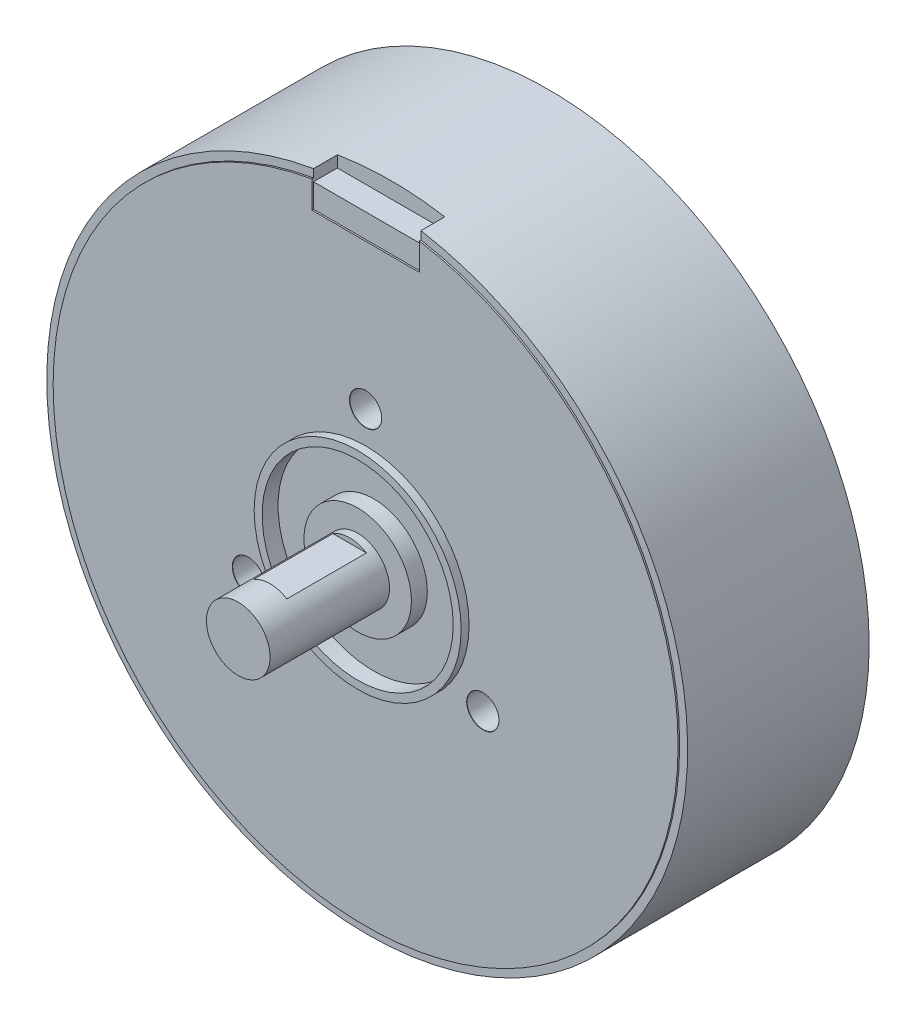
SolidWorks part; units mm, degrees
ref_plane "Front Plane" through (0, 0, 0) normal (0, 0, 1) x (1, 0, 0)
ref_plane "Top Plane" through (0, 0, 0) normal (0, 1, 0) x (1, 0, 0)
ref_plane "Right Plane" through (0, 0, 0) normal (1, 0, 0) x (0, 0, -1)
sketch "Sketch1" plane through (0, 0, 0) normal (0, 0, 1) x (1, 0, 0)
  circle A0 centre (0, 0) radius 40.25
  dimension "D1" = 80.5
extrude "Boss-Extrude1" add sketch "Sketch1" along normal blind 23 contours A0
sketch "Sketch2" plane through (0, 0, 23) normal (0, 0, 1) x (1, 0, 0)
  circle A0 centre (0, 0) radius 12
  dimension "D1" = 24
extrude "Cut-Extrude1" cut sketch "Sketch2" against normal blind 1 contours A0
sketch "Sketch3" plane through (0, 0, 23) normal (0, 0, 1) x (1, 0, 0)
  circle A0 centre (0, 0) radius 13
  circle A1 centre (0, 0) radius 12
  dimension "D1" = 26
  dimension "D2" = 24
extrude "Boss-Extrude2" add sketch "Sketch3" along normal blind 1 contours A0
sketch "Sketch4" plane through (0, 0, 22) normal (0, 0, 1) x (1, 0, 0)
  circle A0 centre (0, 0) radius 6.75
  dimension "D1" = 13.5
extrude "Boss-Extrude3" add sketch "Sketch4" along normal blind 2
sketch "Sketch5" plane through (0, 0, 24) normal (0, 0, 1) x (1, 0, 0)
  line L0 (0, -4) -> (0, 3.4)
  line L1 (4, 0) -> (-3.4, 0)
  line L2 (2.1071, 3.4) -> (-2.1071, 3.4)
  line L3 (-3.4, 2.1071) -> (-3.4, -2.1071)
  circle A0 centre (0, 0) radius 4
  dimension "D1" = 8
  dimension "D2" = 7.4
  dimension "D3" = 7.4
sketch "Sketch7" plane through (0, 0, 24) normal (0, 0, 1) x (1, 0, 0)
  circle A0 centre (0, 0) radius 4
extrude "Boss-Extrude5" add sketch "Sketch7" along normal blind 1
extrude "Boss-Extrude6" add sketch "Sketch5" along normal blind 11 contours L0 A0 L1 | L1 A0 L2 L0 | L2 A0 L3 L1 L0 | L3 A0 L0 L1
sketch "Sketch8" plane through (0, 0, 35) normal (0, 0, 1) x (1, 0, 0)
  circle A0 centre (0, 0) radius 4
extrude "Boss-Extrude7" add sketch "Sketch8" along normal blind 4 contours A0
sketch "Sketch9" plane through (0, 0, 23) normal (0, 0, 1) x (1, 0, 0)
  circle A0 centre (0, 0) radius 39.25
  circle A1 centre (0, 0) radius 40.25
  dimension "D1" = 78.5
extrude "Cut-Extrude2" cut sketch "Sketch9" against normal blind 0.2
sketch "Sketch11" plane through (0, 0, 23) normal (0, 0, 1) x (1, 0, 0)
  line L0 (0, 39.25) -> (0, 35.25)
  line L1 (0, 35.25) -> (6.75, 35.25)
  line L3 (6.75, 35.25) -> (-6.75, 35.25)
  line L4 (6.75, 35.25) -> (6.75, 40.1486)
  line L5 (6.75, 40.1486) -> (-6.75, 40.1486)
  line L6 (-6.75, 35.25) -> (-6.75, 40.1486)
  circle A0 centre (0, 0) radius 39.25 construction
  circle A1 centre (0, 0) radius 39.25 construction
  circle A2 centre (0, 0) radius 39.25
  circle M5 centre (0, 0) radius 39.25
  dimension "D1" = 4
  dimension "D2" = 6.75
  dimension "D3" = 13.5
extrude "Cut-Extrude4" cut sketch "Sketch11" against normal blind 0.2 contours L1 L4 L0 M5 | L6 L3 L0 M5
sketch "Sketch12" plane through (0, 0, 22.8) normal (0, 0, 1) x (1, 0, 0)
  line L1 (6.75, 35.25) -> (-6.75, 35.25)
  line L2 (6.75, 35.25) -> (6.75, 38.25)
  line L3 (6.75, 38.25) -> (-6.75, 38.25)
  line L4 (-6.75, 35.25) -> (-6.75, 38.25)
  line L5 (-6.75, 38.25) -> (6.75, 38.25)
  line L9 (-6.75, 38.25) -> (6.75, 38.25)
  line L10 (-6.75, 38.25) -> (-6.75, 40.2406)
  line L11 (-6.75, 40.2406) -> (6.75, 40.2406)
  line L12 (6.75, 38.25) -> (6.75, 40.2406)
  circle A0 centre (0, 0) radius 40.2577
  line M4 (-6.75, 38.6652) -> (-6.75, 35.25)
  line M6 (6.75, 35.25) -> (6.75, 38.6652)
  circle M7 centre (0, 0) radius 40.25
  dimension "D1" = 3
extrude "Cut-Extrude5" cut sketch "Sketch12" against normal blind 3 contours L12 L11 L10 L3 M6 M7 M4 | L11 M7
sketch "Sketch13" plane through (0, 0, 23) normal (0, 0, 1) x (1, 0, 0)
  line L0 (0, 40.25) -> (0, 0)
  line L1 (0, 0) -> (-14.7224, -8.5)
  line L2 (0, 0) -> (14.7224, -8.5)
  circle A0 centre (0, 0) radius 17
  arc A1 (6.75, 39.68) -> (-6.75, 39.68) centre (0, 0) ccw construction
  point P9 (0, 17)
  point P11 (-14.7224, -8.5)
  point P12 (14.7224, -8.5)
  dimension "D1" = 34
  dimension "D2" = 120
  dimension "D3" = 120
  dimension "D4" = 17
  dimension "D5" = 17
hole_wizard "Ø4.0mm Dowel Hole1" positions "Sketch14" profile "Sketch15" hole size "Ø4.0" standard "ANSI Metric"
sketch "Sketch14" plane through (0, 0, 23) normal (0, 0, 1) x (1, 0, 0)
  point P0 (0, 17)
  point P3 (14.7224, -8.5)
  point P6 (-14.7224, -8.5)
sketch "Sketch15" plane through (0, 17, 23) normal (1, 0, 0) x (0, -1, 0)
  line L0 (0, 0) -> (0, 6.7017)
  line L1 (0, 6.7017) -> (2, 5.5)
  line L2 (2, 5.5) -> (2, 0.025)
  line L3 (2, 0.025) -> (2.025, 0)
  line L5 (2.025, 0) -> (0, 0)
  line L6 (-2, 0.025) -> (-2.025, 0) construction
  line L10 (0, 6.7017) -> (-2, 5.5) construction
  line L11 (0, -6.35) -> (0, 107.95) construction
  dimension "Hole Dia." = 4
  dimension "Hole Depth" = 5.5
  dimension "Near C'Sink Dia." = 4.05
  dimension "Near C'Sink Angle" = 90
  dimension "Drill Angle" = 118
